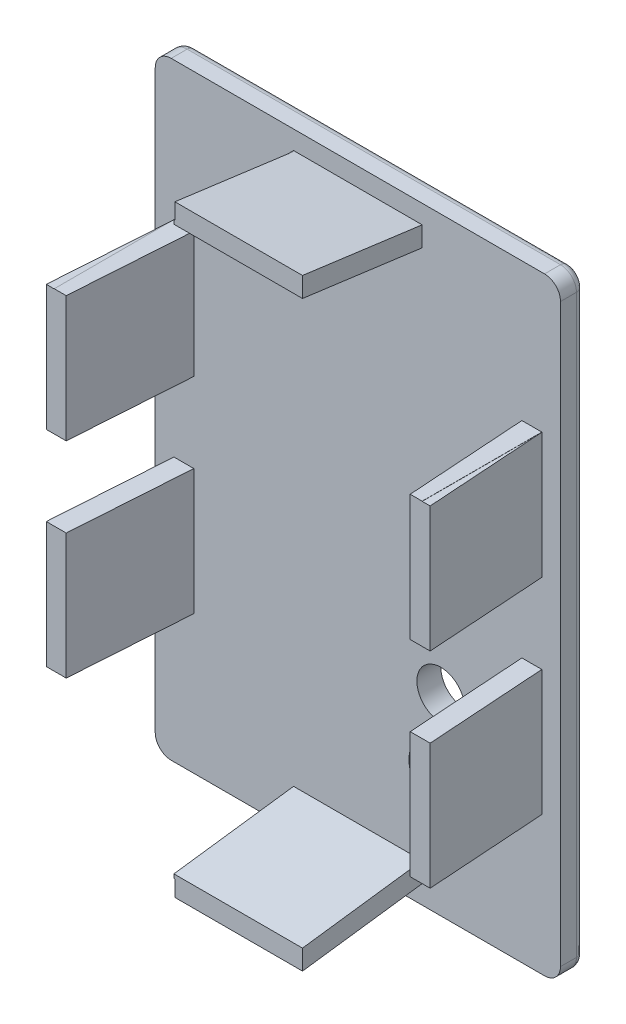
SolidWorks part; units mm, degrees
material "PLA"
ref_plane "Alzado" through (0, 0, 0) normal (0, 0, 1) x (1, 0, 0)
ref_plane "Planta" through (0, 0, 0) normal (0, 1, 0) x (1, 0, 0)
ref_plane "Vista lateral" through (0, 0, 0) normal (1, 0, 0) x (0, 0, -1)
sketch "Croquis1" plane through (0, 0, 0) normal (0, 0, 1) x (1, 0, 0)
  line L1 (25.4, 38.1) -> (-25.4, 38.1)
  line L2 (25.4, 38.1) -> (25.4, -38.1)
  line L3 (25.4, -38.1) -> (-25.4, -38.1)
  line L4 (-25.4, 38.1) -> (-25.4, -38.1)
  line L5 (25.4, 38.1) -> (-25.4, -38.1) construction
  line L6 (25.4, -38.1) -> (-25.4, 38.1) construction
  point P0 (0, 0)
  dimension "D1" = 76.2
  dimension "D2" = 50.8
extrude "Saliente-Extruir1" add sketch "Croquis1" along normal blind 18
sketch "Croquis2" plane through (0, 0, 18) normal (0, 0, 1) x (1, 0, 0)
  line L0 (25.4, 38.1) -> (-25.4, 38.1) construction
  line L1 (-23.06, 35.76) -> (23.06, 35.76)
  line L2 (-23.06, 35.76) -> (-23.06, -35.76)
  line L3 (-23.06, -35.76) -> (23.06, -35.76)
  line L4 (23.06, 35.76) -> (23.06, -35.76)
  line L5 (-25.4, -38.1) -> (25.4, -38.1) construction
  line L6 (-25.4, 38.1) -> (-25.4, -38.1) construction
  line L7 (25.4, -38.1) -> (25.4, 38.1) construction
  line L9 (-25.4, 38.1) -> (25.4, 38.1)
  line L10 (-25.4, 38.1) -> (-25.4, -38.1)
  line L11 (-25.4, -38.1) -> (25.4, -38.1)
  line L12 (25.4, 38.1) -> (25.4, -38.1)
  line L13 (-19.4, 32.1) -> (19.4, 32.1)
  line L14 (-19.4, 32.1) -> (-19.4, -32.1)
  line L15 (-19.4, -32.1) -> (19.4, -32.1)
  line L16 (19.4, 32.1) -> (19.4, -32.1)
  line M9 (-25.4, 38.1) -> (-25.4, -38.1)
  line M10 (-25.4, -38.1) -> (25.4, -38.1)
  line M11 (25.4, -38.1) -> (25.4, 38.1)
  line M12 (25.4, 38.1) -> (-25.4, 38.1)
  dimension "D1" = 2.34
  dimension "D2" = 2.34
  dimension "D3" = 2.34
  dimension "D4" = 2.34
  dimension "D5" = 6
  dimension "D6" = 6
  dimension "D7" = 6
  dimension "D8" = 6
extrude "Cortar-Extruir1" cut sketch "Croquis2" against normal blind 15 contours L1 L4 L3 L2 M12 M9 M10 M11 | L16 L13 L14 L15
sketch "Croquis3" plane through (0, 0, 18) normal (0, 0, 1) x (1, 0, 0)
  line L0 (-23.06, 35.76) -> (-23.06, -35.76) construction
  line L1 (-23.06, 22.1) -> (-19.4, 22.1)
  line L2 (-23.06, 22.1) -> (-23.06, -22.1)
  line L3 (-23.06, -22.1) -> (-19.4, -22.1)
  line L4 (-19.4, 22.1) -> (-19.4, -22.1)
  line L5 (-19.4, 32.1) -> (-19.4, -32.1) construction
  line L6 (-19.4, -32.1) -> (19.4, -32.1) construction
  line L7 (-9.4, -32.1) -> (9.3837, -32.1)
  line L8 (-9.4, -32.1) -> (-9.4, -35.76)
  line L9 (-9.4, -35.76) -> (9.3837, -35.76)
  line L10 (9.3837, -32.1) -> (9.3837, -35.76)
  line L11 (-23.06, -35.76) -> (23.06, -35.76) construction
  line L12 (19.4, 32.1) -> (19.4, -32.1) construction
  line L13 (19.4, -22.1) -> (23.06, -22.1)
  line L14 (19.4, -22.1) -> (19.4, 22.1)
  line L15 (19.4, 22.1) -> (23.06, 22.1)
  line L16 (23.06, -22.1) -> (23.06, 22.1)
  line L17 (23.06, 35.76) -> (23.06, -35.76) construction
  line L18 (-23.06, 35.76) -> (23.06, 35.76) construction
  line L19 (-9.4, 35.76) -> (9.4, 35.76)
  line L20 (-9.4, 35.76) -> (-9.4, 32.1)
  line L21 (-9.4, 32.1) -> (9.4, 32.1)
  line L22 (9.4, 35.76) -> (9.4, 32.1)
  line L23 (-19.4, 32.1) -> (19.4, 32.1) construction
  line L24 (-19.4, 32.1) -> (-19.4, -32.1) construction
  line L25 (19.4, 32.1) -> (19.4, -32.1) construction
  dimension "D1" = 10
  dimension "D2" = 10
  dimension "D3" = 10
  dimension "D4" = 10
  dimension "D5" = 10
  dimension "D6" = 10
  dimension "D7" = 10
extrude "Cortar-Extruir2" [suppressed] cut sketch "Croquis3" against normal blind 7
fillet "Redondeo1" [suppressed] radius 2
fillet "Redondeo2" [suppressed] radius 1
sketch "Croquis5" [suppressed] plane through (0, -38.1, 0) normal (0, -1, 0) x (1, 0, 0)
  line L0 (-23.4, 3) -> (23.4, 3) construction
  line L1 (-3, 3) -> (3, 3)
  line L2 (-3, 3) -> (-3, 1.5)
  line L3 (-3, 1.5) -> (3, 1.5)
  line L4 (3, 3) -> (3, 1.5)
  line L5 (0, 1) -> (0, 3) construction
  line L6 (-23.4, 1) -> (23.4, 1) construction
  dimension "D1" = 3
  dimension "D2" = 3
  dimension "D3" = 1.5
extrude "Cortar-Extruir4" [suppressed] cut sketch "Croquis5" against normal blind 6
sketch "Croquis6" plane through (0, 0, 18) normal (0, 0, 1) x (1, 0, 0)
  line L0 (-23.06, 35.76) -> (-8.06, 35.76)
  line L1 (-23.06, 35.76) -> (23.06, 35.76) construction
  line L2 (-8.06, 35.76) -> (-8.06, 32.1)
  line L3 (-19.4, 32.1) -> (19.4, 32.1) construction
  line L4 (-8.06, 32.1) -> (-19.4, 32.1)
  line L5 (-19.4, 32.1) -> (-19.4, 20.76)
  line L6 (-19.4, 32.1) -> (-19.4, -32.1) construction
  line L7 (-19.4, 20.76) -> (-23.06, 20.76)
  line L8 (-23.06, 35.76) -> (-23.06, -35.76) construction
  line L9 (-23.06, 20.76) -> (-23.06, 35.76)
  line L10 (23.06, 35.76) -> (8.06, 35.76)
  line L11 (-23.06, 35.76) -> (23.06, 35.76) construction
  line L12 (8.06, 35.76) -> (8.06, 32.1)
  line L13 (8.06, 32.1) -> (19.4, 32.1)
  line L14 (19.4, 32.1) -> (19.4, -32.1) construction
  line L15 (19.4, 32.1) -> (19.4, -32.1) construction
  line L16 (19.4, 32.1) -> (19.4, 20.76)
  line L17 (19.4, 20.76) -> (23.06, 20.76)
  line L18 (23.06, 35.76) -> (23.06, -35.76) construction
  line L19 (23.06, 20.76) -> (23.06, 35.76)
  line L20 (-23.06, -35.76) -> (-23.06, -20.76)
  line L21 (-23.06, 35.76) -> (-23.06, -35.76) construction
  line L22 (-23.06, -20.76) -> (-19.4, -20.76)
  line L23 (-19.4, 32.1) -> (-19.4, -32.1) construction
  line L24 (-19.4, -20.76) -> (-19.4, -32.1)
  line L25 (-19.4, -32.1) -> (-8.06, -32.1)
  line L26 (-19.4, -32.1) -> (19.4, -32.1) construction
  line L27 (-8.06, -32.1) -> (-8.06, -35.76)
  line L28 (-23.06, -35.76) -> (23.06, -35.76) construction
  line L29 (-8.06, -35.76) -> (-23.06, -35.76)
  line L30 (23.06, -35.76) -> (8.06, -35.76)
  line L31 (-23.06, -35.76) -> (23.06, -35.76) construction
  line L32 (8.06, -35.76) -> (8.06, -32.1)
  line L33 (-19.4, -32.1) -> (19.4, -32.1) construction
  line L34 (8.06, -32.1) -> (19.4, -32.1)
  line L35 (19.4, -32.1) -> (19.4, -20.76)
  line L36 (19.4, -20.76) -> (23.06, -20.76)
  line L37 (23.06, 35.76) -> (23.06, -35.76) construction
  line L38 (23.06, -20.76) -> (23.06, -35.76)
  dimension "D1" = 15
  dimension "D2" = 15
  dimension "D3" = 15
  dimension "D4" = 15
  dimension "D5" = 15
  dimension "D6" = 15
  dimension "D7" = 15
  dimension "D8" = 15
extrude "Cortar-Extruir8" cut sketch "Croquis6" against normal blind 15
sketch "Croquis10" plane through (0, -20.76, 0) normal (0, -1, 0) x (-1, 0, 0)
  line L0 (23.06, -18) -> (24.06, -18)
  line L1 (24.06, -18) -> (23.06, -3)
  line L2 (23.06, -3) -> (23.06, -18)
  line L3 (-23.06, -18) -> (-24.06, -18)
  line L4 (-24.06, -18) -> (-23.06, -3)
  line L5 (-23.06, -3) -> (-23.06, -18)
  dimension "D1" = 1
  dimension "D2" = 1
extrude "Saliente-Extruir3" add sketch "Croquis10" against normal blind 41.5
sketch "Croquis11" plane through (0, -20.76, 0) normal (0, -1, 0) x (1, 0, 0)
  line L0 (-19.4, 18) -> (-21.56, 18)
  line L1 (-19.4, 18) -> (-24.06, 18) construction
  line L2 (-21.56, 18) -> (-20.56, 3)
  line L3 (-19.4, 3) -> (-23.06, 3) construction
  line L4 (-20.56, 3) -> (-19.4, 3)
  line L5 (-19.4, 18) -> (-19.4, 3)
  dimension "D1" = 2.5
  dimension "D2" = 1.16
extrude "Cortar-Extruir9" cut sketch "Croquis11" against normal blind 51.5
sketch "Croquis12" plane through (0, -20.76, 0) normal (0, -1, 0) x (1, 0, 0)
  line L0 (19.4, 18) -> (19.4, 3)
  line L1 (19.4, 3) -> (20.56, 3)
  line L2 (23.06, 3) -> (19.4, 3) construction
  line L3 (20.56, 3) -> (21.56, 18)
  line L4 (24.06, 18) -> (19.4, 18) construction
  line L5 (21.56, 18) -> (19.4, 18)
  dimension "D1" = 2.5
  dimension "D2" = 1.16
extrude "Cortar-Extruir10" cut sketch "Croquis12" against normal blind 51.5
sketch "Croquis13" plane through (8.06, 0, 0) normal (1, 0, 0) x (0, 0, -1)
  line L0 (-18, -35.76) -> (-18, -37.76)
  line L1 (-18, -37.76) -> (-3, -35.76)
  line L2 (-3, -35.76) -> (-18, -35.76)
  line L3 (-18, 35.76) -> (-18, 37.76)
  line L4 (-18, 37.76) -> (-3, 35.76)
  line L5 (-3, 35.76) -> (-18, 35.76)
  dimension "D1" = 2
  dimension "D2" = 2
extrude "Saliente-Extruir4" add sketch "Croquis13" against normal blind 16
sketch "Croquis14" plane through (8.06, 0, 0) normal (1, 0, 0) x (0, 0, -1)
  line L0 (-3, -32.1) -> (-18, -32.1)
  line L1 (-18, -32.1) -> (-18, -35.26)
  line L2 (-18, -32.1) -> (-18, -37.76) construction
  line L3 (-18, -35.26) -> (-3, -33.26)
  line L4 (-3, -32.1) -> (-3, -35.76) construction
  line L5 (-3, -33.26) -> (-3, -32.1)
  line L6 (-18, 32.1) -> (-18, 35.26)
  line L7 (-18, 37.76) -> (-18, 32.1) construction
  line L8 (-18, 35.26) -> (-3, 33.26)
  line L9 (-3, 35.76) -> (-3, 32.1) construction
  line L10 (-3, 33.26) -> (-3, 32.1)
  line L11 (-3, 32.1) -> (-18, 32.1)
  dimension "D1" = 2.5
  dimension "D2" = 1.16
  dimension "D3" = 2.5
  dimension "D4" = 1.16
extrude "Cortar-Extruir11" cut sketch "Croquis14" against normal blind 16.5
fillet "Redondeo3" radius 2 4 edges at (25.4, 38.1, 1.5) (-25.4, 38.1, 1.5) (-25.4, -38.1, 1.5) (25.4, -38.1, 1.5)
fillet "Redondeo4" radius 1 8 edges at (-24.8142, 37.5142, 0) (-25.4, 0, 0) (-24.8142, -37.5142, 0) (0, -38.1, 0) (24.8142, -37.5142, 0) (25.4, 0, 0) (24.8142, 37.5142, 0) (0, 38.1, 0)
sketch "Croquis15" plane through (0, 0, 18) normal (0, 0, 1) x (1, 0, 0)
  line L0 (-24.06, -0.01) -> (24.06, -0.01) construction
  line L1 (-24.06, 20.74) -> (-24.06, -20.76) construction
  line L2 (24.06, 20.74) -> (24.06, -20.76) construction
  line L4 (-24.06, 4.99) -> (24.06, 4.99)
  line L5 (-24.06, 4.99) -> (-24.06, -5.01)
  line L6 (-24.06, -5.01) -> (24.06, -5.01)
  line L7 (24.06, 4.99) -> (24.06, -5.01)
  dimension "D1" = 5
  dimension "D2" = 5
extrude "Cortar-Extruir12" cut sketch "Croquis15" against normal blind 15
sketch "Croquis16" plane through (0, -38.1, 0) normal (0, -1, 0) x (1, 0, 0)
  line L0 (-23.4, 3) -> (23.4, 3) construction
  line L1 (-4, 3) -> (4, 3)
  line L2 (-4, 3) -> (-4, 1.5)
  line L3 (-4, 1.5) -> (4, 1.5)
  line L4 (4, 3) -> (4, 1.5)
  dimension "D1" = 1.5
  dimension "D2" = 8
  dimension "D3" = 4
extrude "Cortar-Extruir13" cut sketch "Croquis16" against normal blind 2
sketch "Croquis17" plane through (0, 0, 3) normal (0, 0, 1) x (1, 0, 0)
  line L1 (-23.4, -38.1) -> (-4, -38.1) construction
  line L2 (25.4, -36.1) -> (25.4, 36.1) construction
  circle A0 centre (10.4, -23.1) radius 4
  circle A1 centre (10.4, -14.1) radius 3
  dimension "D3" = 8
  dimension "D4" = 6
  dimension "D1" = 15
  dimension "D2" = 15
  dimension "D7" = 9
  dimension "D8" = 15
extrude "Cortar-Extruir14" cut sketch "Croquis17" against normal blind 10
